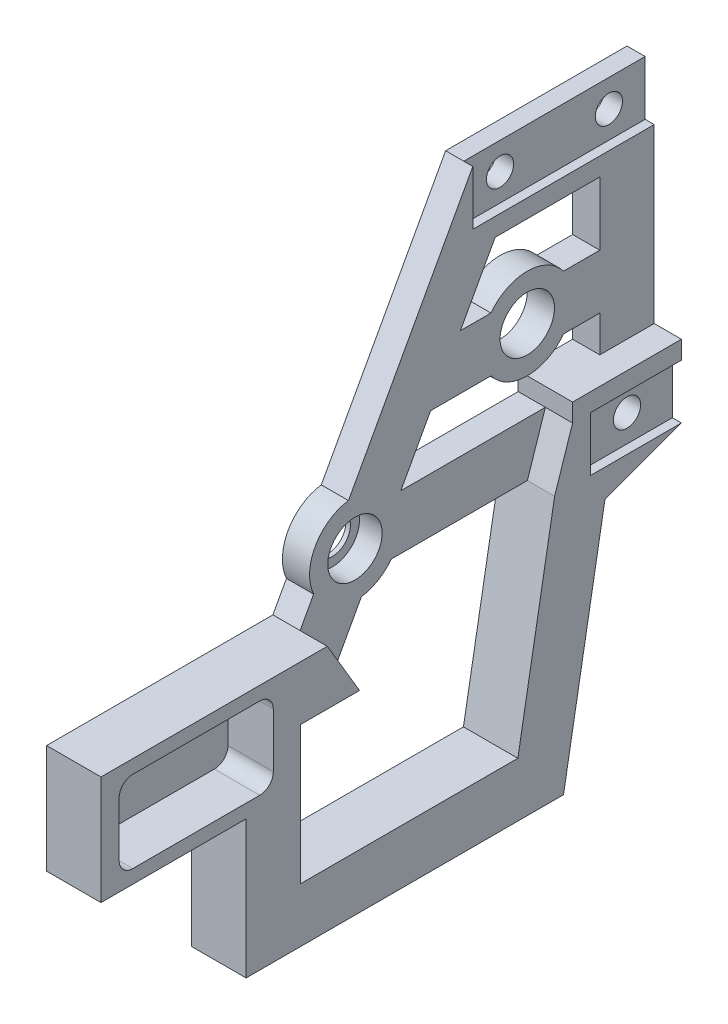
SolidWorks part; units mm, degrees
material "1060 Alloy"
ref_plane "Front Plane" through (0, 0, 0) normal (0, 0, 1) x (1, 0, 0)
ref_plane "Top Plane" through (0, 0, 0) normal (0, 1, 0) x (1, 0, 0)
ref_plane "Right Plane" through (0, 0, 0) normal (1, 0, 0) x (0, 0, -1)
sketch "Sketch1" plane through (0, 0, 0) normal (1, 0, 0) x (0, 0, -1)
  line L0 (51, 0) -> (55.5726, 25.9327)
  line L1 (16, 0) -> (51, 0)
  line L2 (0, 15.2) -> (0, 27.2)
  line L3 (44, 62) -> (64, 62)
  line L4 (64, 29) -> (64, 62)
  line L5 (55.5726, 25.9327) -> (64, 29)
  line L6 (16, 0) -> (16, 15.2)
  line L7 (16, 15.2) -> (0, 15.2)
  line L8 (0, 27.2) -> (24.9528, 27.2)
  line L9 (44, 62) -> (30.2889, 36.9492)
  line L10 (44, 62) -> (44, 56) construction
  line L11 (44, 56) -> (64, 56) construction
  line L12 (64, 29) -> (54, 29) construction
  line L13 (54, 29) -> (54, 35) construction
  line L14 (54, 35) -> (64, 35) construction
  line L15 (31, 32) -> (44, 55.7516) construction
  line L16 (39.346, 41) -> (36.062, 35)
  line L17 (31, 32) -> (59, 32) construction
  line L18 (50, 44) -> (64, 44) construction
  line L19 (39.346, 41) -> (46, 41)
  line L20 (46.4613, 54) -> (42.6299, 47)
  line L21 (42.6299, 47) -> (46, 47)
  line L22 (54, 47) -> (58, 47)
  line L23 (58, 47) -> (58, 54)
  line L24 (58, 54) -> (46.4613, 54)
  line L25 (54, 41) -> (58, 41)
  line L26 (58, 41) -> (58, 37)
  line L27 (58, 37) -> (52, 37)
  line L28 (52, 37) -> (52, 35)
  line L29 (52, 35) -> (36.062, 35)
  line L30 (35, 29) -> (50.0209, 29)
  line L31 (28.5088, 21.2) -> (31.7111, 27.0508)
  line L32 (50.0209, 29) -> (45.9654, 6)
  line L33 (45.9654, 6) -> (22, 6)
  line L34 (22, 6) -> (22, 21.2)
  line L35 (22, 21.2) -> (28.5088, 21.2)
  line L36 (26.4479, 29.9316) -> (24.9528, 27.2)
  circle A0 centre (59, 32) radius 1.5
  circle A1 centre (50, 44) radius 3
  circle A2 centre (60, 59) radius 1.5
  circle A3 centre (48, 59) radius 1.5
  circle A4 centre (31, 32) radius 2
  circle A5 centre (31, 32) radius 5 construction
  arc A6 (46, 47) -> (54, 47) centre (50, 44) cw
  arc A7 (46, 41) -> (54, 41) centre (50, 44) ccw
  arc A8 (31.7111, 27.0508) -> (35, 29) centre (31, 32) ccw
  arc A9 (30.2889, 36.9492) -> (26.4479, 29.9316) centre (31, 32) ccw
  dimension "D1" = 6
  dimension "D2" = 16
  dimension "D4" = 3
  dimension "D14" = 4
  dimension "D24" = 10
  dimension "D27" = 5
  dimension "D3" = 15.2
  dimension "D5" = 44
  dimension "D6" = 50
  dimension "D7" = 64
  dimension "D8" = 62
  dimension "D9" = 4
  dimension "D10" = 12
  dimension "D11" = 3
  dimension "D12" = 3
  dimension "D13" = 5
  dimension "D15" = 12
  dimension "D16" = 32
  dimension "D17" = 31
  dimension "D18" = 32
  dimension "D19" = 6
  dimension "D20" = 20
  dimension "D21" = 10
  dimension "D22" = 6
  dimension "D23" = 51
  dimension "D25" = 6
  dimension "D26" = 3
  dimension "D28" = 6
  dimension "D29" = 3
  dimension "D30" = 6
  dimension "D31" = 6
  dimension "D32" = 3
  dimension "D33" = 2
  dimension "D34" = 2
  dimension "D35" = 2
  dimension "D36" = 6
  dimension "D37" = 6
  dimension "D38" = 20
  dimension "D39" = 100
  dimension "D40" = 6
  dimension "D41" = 6
extrude "Boss-Extrude1" add sketch "Sketch1" along normal blind 6
hole_wizard "Tap Drill for M3 Tap1" positions "Sketch5" profile "Sketch4" hole size "M3" standard "ISO"
sketch "Sketch5" plane through (0, 0, 0) normal (0, -1, 0) x (-1, 0, 0)
  line L0 (0, 16) -> (0, 51) construction
  line L2 (-6, 51) -> (0, 51) construction
  line L4 (-6, 16) -> (0, 16) construction
  point P0 (-3, 48)
  point P2 (-3, 19)
  dimension "D1" = 3
  dimension "D2" = 3
  dimension "D3" = 3
sketch "Sketch4" plane through (3, 0, -48) normal (1, 0, 0) x (0, 0, -1)
  line L0 (0, 0) -> (0, 9.7511)
  line L1 (0, 9.7511) -> (1.25, 9)
  line L2 (1.25, 9) -> (1.25, 0)
  line L5 (1.25, 0) -> (0, 0)
  line L10 (0, 9.7511) -> (-1.25, 9) construction
  line L11 (0, -6.35) -> (0, 107.95) construction
  dimension "Hole Dia." = 2.5
  dimension "Hole Depth" = 9
  dimension "Drill Angle" = 118
sketch "Sketch13" plane through (6, 0, 0) normal (1, 0, 0) x (0, 0, -1)
  line L0 (64, 29) -> (64, 62) construction
  line L1 (52, 37) -> (64, 37)
  line L2 (64, 62) -> (44, 62) construction
  line L3 (64, 62) -> (44, 62)
  line L4 (64, 37) -> (64, 62)
  line L5 (30.2889, 36.9492) -> (28.0089, 36.9492)
  line L6 (28.0089, 36.9492) -> (23.7675, 29.2)
  line L7 (36.062, 35) -> (52, 35) construction
  line L8 (52, 35) -> (52, 37)
  line L9 (52, 35) -> (52, 37) construction
  line L10 (23.7675, 29.2) -> (28.5088, 21.2)
  line L11 (44, 62) -> (30.2889, 36.9492)
  line L12 (28.5088, 21.2) -> (50.0209, 29)
  line L13 (44, 62) -> (30.2889, 36.9492) construction
  line L14 (50.0209, 29) -> (52, 35)
  arc A2 (30.2889, 36.9492) -> (26.4479, 29.9316) centre (31, 32) ccw construction
  dimension "D3" = 25
extrude "Cut-Extrude4" cut sketch "Sketch13" against normal blind 3
sketch "Sketch14" plane through (3, 0, 0) normal (1, 0, 0) x (0, 0, -1)
  line L1 (64, 62) -> (44, 62)
  line L2 (64, 62) -> (64, 56)
  line L3 (64, 56) -> (44, 56)
  line L4 (44, 62) -> (44, 56)
  dimension "D1" = 6
extrude "Cut-Extrude5" cut sketch "Sketch14" against normal blind 1
sketch "Sketch15" plane through (6, 0, 0) normal (1, 0, 0) x (0, 0, -1)
  line L1 (64, 29) -> (54, 29)
  line L2 (64, 29) -> (64, 35)
  line L3 (64, 35) -> (54, 35)
  line L4 (54, 29) -> (54, 35)
  dimension "D1" = 10
  dimension "D2" = 6
extrude "Cut-Extrude6" cut sketch "Sketch15" against normal blind 1
sketch "Sketch16" plane through (3, 0, 0) normal (1, 0, 0) x (0, 0, -1)
  circle A0 centre (31, 32) radius 3
  dimension "D1" = 6
extrude "Cut-Extrude7" cut sketch "Sketch16" against normal blind 2.5
sketch "Sketch17" plane through (6, 0, 0) normal (1, 0, 0) x (0, 0, -1)
  line L0 (0, 27.2) -> (0, 15.2) construction
  line L1 (2, 25.7) -> (19, 25.7)
  line L2 (2, 25.7) -> (2, 16.7)
  line L3 (2, 16.7) -> (19, 16.7)
  line L4 (19, 25.7) -> (19, 16.7)
  line L5 (24.9528, 27.2) -> (0, 27.2) construction
  line L6 (0, 15.2) -> (16, 15.2) construction
  line L7 (22, 21.2) -> (22, 6) construction
  dimension "D1" = 2
  dimension "D2" = 1.5
  dimension "D3" = 1.5
  dimension "D4" = 3
extrude "Cut-Extrude8" cut sketch "Sketch17" against normal offset from surface (5 mm away) 1 up to face at (0, 38.25, -49.426)
fillet "Fillet1" radius 1.5 4 edges at (3.5, 25.7, -2) (3.5, 16.7, -2) (3.5, 16.7, -19) (3.5, 25.7, -19)
